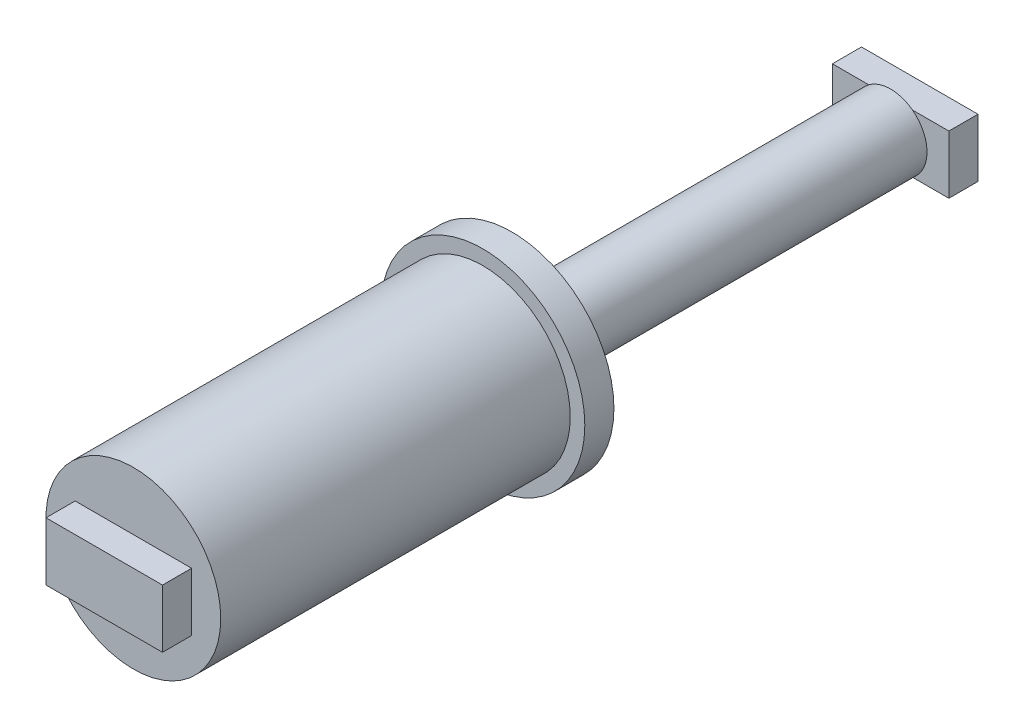
SolidWorks part; units mm, degrees
ref_plane "Front Plane" through (0, 0, 0) normal (0, 0, 1) x (1, 0, 0)
ref_plane "Top Plane" through (0, 0, 0) normal (0, 1, 0) x (1, 0, 0)
ref_plane "Right Plane" through (0, 0, 0) normal (1, 0, 0) x (0, 0, -1)
sketch "Sketch1" plane through (0, 0, 0) normal (0, 0, 1) x (1, 0, 0)
  circle A0 centre (0, 0) radius 12.5
  dimension "D1" = 25
extrude "Boss-Extrude1" add sketch "Sketch1" along normal blind 130
sketch "Sketch2" plane through (0, 0, 130) normal (0, 0, 1) x (1, 0, 0)
  circle A0 centre (0, 0) radius 35
  dimension "D1" = 70
extrude "Boss-Extrude2" add sketch "Sketch2" along normal blind 10
sketch "Sketch3" plane through (0, 0, 140) normal (0, 0, 1) x (1, 0, 0)
  circle A0 centre (0, 0) radius 30
extrude "Boss-Extrude3" add sketch "Sketch3" along normal blind 120
sketch "Sketch4" plane through (0, 0, 0) normal (0, 0, -1) x (-1, 0, 0)
  line L1 (20, 10) -> (-20, 10)
  line L2 (20, 10) -> (20, -10)
  line L3 (20, -10) -> (-20, -10)
  line L4 (-20, 10) -> (-20, -10)
  line L5 (20, 10) -> (-20, -10) construction
  line L6 (20, -10) -> (-20, 10) construction
  point P0 (0, 0)
  dimension "D1" = 20
  dimension "D2" = 40
extrude "Boss-Extrude4" add sketch "Sketch4" along normal blind 10
ref_plane "Middle Plane" through (0, 0, 65) normal (0, 0, 1) x (1, 0, 0)
sketch "Schizzo1" plane through (0, 0, 260) normal (0, 0, 1) x (1, 0, 0)
  line L1 (20, -10) -> (-20, -10)
  line L2 (20, -10) -> (20, 10)
  line L3 (20, 10) -> (-20, 10)
  line L4 (-20, -10) -> (-20, 10)
  line L5 (20, -10) -> (-20, 10) construction
  line L6 (20, 10) -> (-20, -10) construction
  point P0 (0, 0)
  dimension "D1" = 20
  dimension "D2" = 40
extrude "Boss-Extrude5" add sketch "Schizzo1" along normal blind 10
